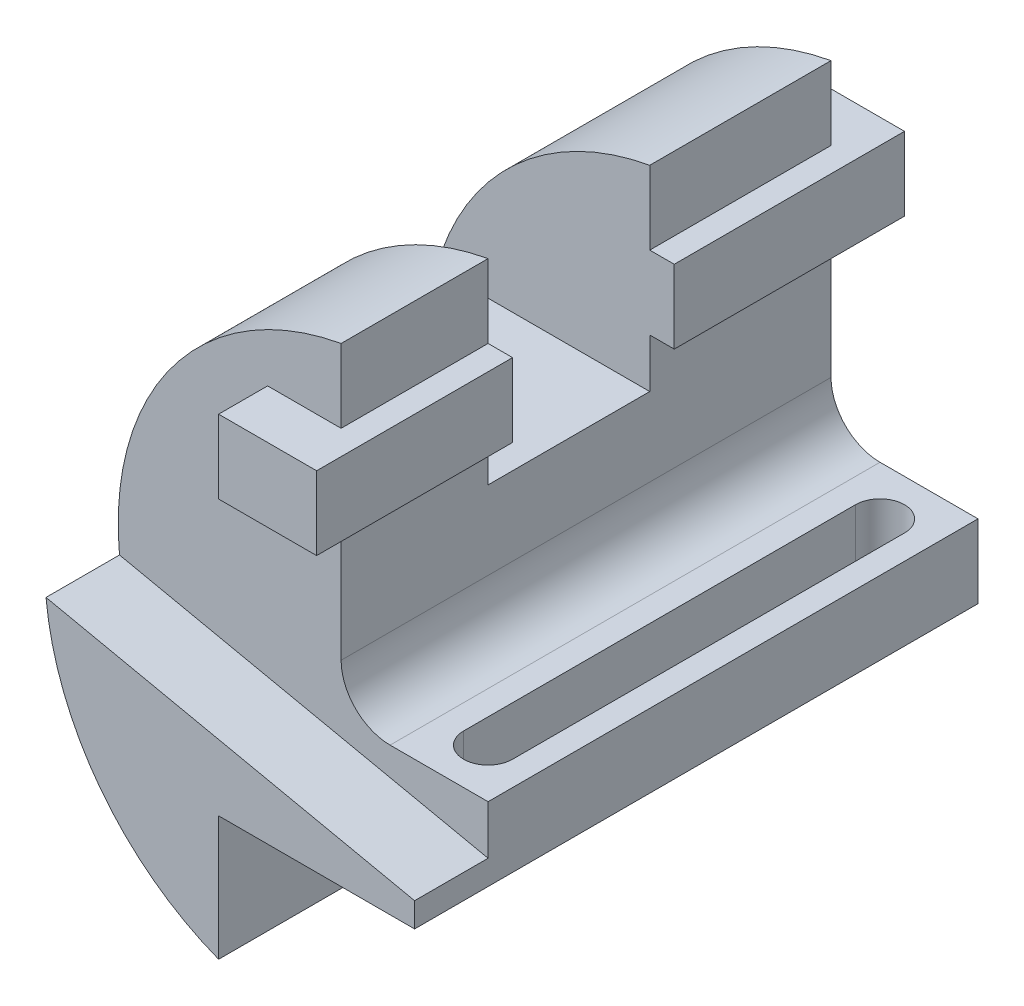
SolidWorks part; units mm, degrees
material "1060 Alloy"
ref_plane "Front Plane" through (0, 0, 0) normal (0, 0, 1) x (1, 0, 0)
ref_plane "Top Plane" through (0, 0, 0) normal (0, 1, 0) x (1, 0, 0)
ref_plane "Right Plane" through (0, 0, 0) normal (1, 0, 0) x (0, 0, -1)
sketch "Sketch1" plane through (0, 0, 0) normal (0, 0, 1) x (1, 0, 0)
  line L0 (0, 0) -> (40, 0)
  line L1 (40, 0) -> (40, 15)
  line L2 (40, 15) -> (10, 15)
  line L3 (10, 15) -> (10, 51)
  line L4 (0, 0) -> (0, -25.3628)
  line L5 (10, 66) -> (15, 66)
  line L6 (15, 66) -> (15, 51)
  line L7 (15, 51) -> (10, 51)
  line L8 (10, 66) -> (10, 81)
  arc A0 (10, 81) -> (0, -25.3628) centre (20, 26.4083) ccw
  dimension "D5" = 55.5
  dimension "D1" = 40
  dimension "D2" = 15
  dimension "D3" = 30
  dimension "D4" = 10
  dimension "D6" = 66
  dimension "D7" = 15
  dimension "D8" = 5
  dimension "D9" = 15
extrude "Boss-Extrude1" add sketch "Sketch1" along normal blind 100
fillet "Fillet1" radius 10 1 edges at (10, 15, 50)
sketch "Sketch2" plane through (0, 0, 100) normal (0, 0, 1) x (1, 0, 0)
  line L0 (40, 5) -> (-35.235, 20.9917)
  line L1 (40, 0) -> (40, 15) construction
  line L2 (40, 5) -> (40, 0)
  line L3 (40, 0) -> (0, 0)
  line L4 (0, 0) -> (0, -25.3628)
  arc A0 (10, 81) -> (0, -25.3628) centre (20, 26.4083) ccw construction
  arc A1 (-35.235, 20.9917) -> (0, -25.3628) centre (20, 26.4083) ccw
  dimension "D1" = 5
  dimension "D2" = 78
extrude "Boss-Extrude2" add sketch "Sketch2" along normal blind 15
sketch "Sketch3" plane through (0, 0, 0) normal (0, 0, 1) x (1, 0, 0)
  line L1 (15, 66) -> (-5, 66)
  line L2 (15, 66) -> (15, 51)
  line L3 (15, 51) -> (-5, 51)
  line L4 (-5, 66) -> (-5, 51)
  point P5 (0, 0)
  dimension "D1" = 20
  dimension "D2" = 15
extrude "Boss-Extrude3" add sketch "Sketch3" against normal blind 10
sketch "Sketch4" plane through (0, 0, 100) normal (0, 0, 1) x (1, 0, 0)
  line L1 (15, 66) -> (-5, 66)
  line L2 (15, 66) -> (15, 51)
  line L3 (15, 51) -> (-5, 51)
  line L4 (-5, 66) -> (-5, 51)
  dimension "D1" = 15
  dimension "D2" = 20
extrude "Boss-Extrude4" add sketch "Sketch4" along normal blind 10
sketch "Sketch5" plane through (0, 0, 0) normal (1, 0, 0) x (0, 0, -1)
  line L0 (-100, 81) -> (0, 81) construction
  line L1 (-70, 81) -> (-37, 81)
  line L2 (-70, 81) -> (-70, 41)
  line L3 (-70, 41) -> (-37, 41)
  line L4 (-37, 81) -> (-37, 41)
  line L5 (-100, 66) -> (-100, 81) construction
  dimension "D1" = 33
  dimension "D2" = 40
  dimension "D3" = 30
extrude "Cut-Extrude2" cut sketch "Sketch5" against normal through all both and the other way through all
sketch "Sketch6" plane through (0, 0, 0) normal (0, 1, 0) x (1, 0, 0)
  line L0 (30, -10) -> (30, -90) construction
  line L1 (35, -10) -> (35, -90)
  line L2 (25, -10) -> (25, -90)
  line L3 (40, -100) -> (40, 0) construction
  arc A0 (35, -10) -> (25, -10) centre (30, -10) ccw
  arc A1 (25, -90) -> (35, -90) centre (30, -90) ccw
  point P2 (30, -50)
  dimension "D3" = 5
  dimension "D1" = 80
  dimension "D2" = 10
  dimension "D4" = 10
extrude "Cut-Extrude3" cut sketch "Sketch6" against normal blind 10 and the other way through all
equation "\"a\"= 55.5mm"
equation "\"b\"= 66mm"
equation "\"c\"= 33mm"
